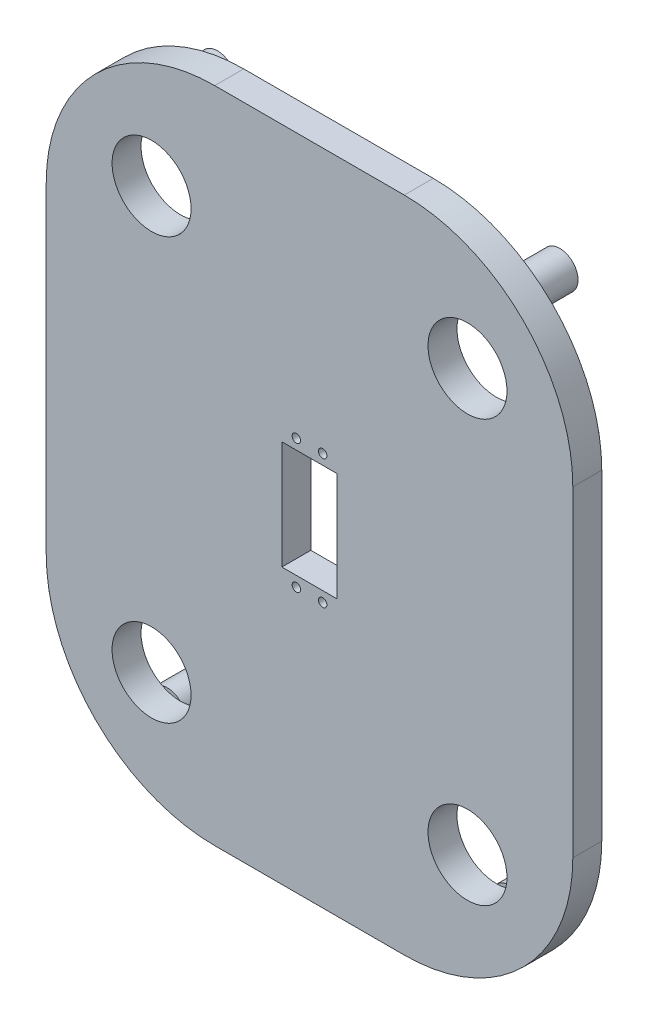
SolidWorks part; units mm, degrees
ref_plane "Front Plane" through (0, 0, 0) normal (0, 0, 1) x (1, 0, 0)
ref_plane "Top Plane" through (0, 0, 0) normal (0, 1, 0) x (1, 0, 0)
ref_plane "Right Plane" through (0, 0, 0) normal (1, 0, 0) x (0, 0, -1)
sketch "Sketch1" plane through (0, 0, 0) normal (0, 0, 1) x (1, 0, 0)
  line L0 (-20, 10) -> (15, 10) construction
  line L2 (-20, 70) -> (-20, -50)
  line L4 (15, 70) -> (15, -50)
  line L5 (-13, 75.5) -> (8, 75.5)
  line L6 (-13, 75.5) -> (-13, 34.5)
  line L7 (-13, 34.5) -> (8, 34.5)
  line L8 (8, 75.5) -> (8, 34.5)
  line L9 (-2.5, 75.5) -> (-2.5, 79.5) construction
  line L10 (-2.5, 79.5) -> (-7.5, 79.5) construction
  line L11 (-2.5, 79.5) -> (2.5, 79.5) construction
  line L12 (-13, 55) -> (8, 55) construction
  line L13 (-7.5, 79.5) -> (-7.5, 30.5) construction
  arc A3 (15, 70) -> (-20, 70) centre (-2.5, 70) ccw
  arc A4 (-20, -50) -> (15, -50) centre (-2.5, -50) ccw
  circle A5 centre (-7.5, 79.5) radius 1.6
  circle A6 centre (2.5, 79.5) radius 1.6
  circle A7 centre (2.5, 30.5) radius 1.6
  circle A8 centre (-7.5, 30.5) radius 1.6
  point P0 (0, 0)
  point P7 (-2.5, 87.5)
  dimension "D4" = 41
  dimension "D5" = 21
  dimension "D7" = 12
  dimension "D11" = 3.2
  dimension "D1" = 120
  dimension "D2" = 35
  dimension "D3" = 120
  dimension "D6" = 7
  dimension "D8" = 4
  dimension "D10" = 5
sketch "Sketch2" plane through (0, 0, 0) normal (0, 0, 1) x (1, 0, 0)
sketch "Sketch3" plane through (0, 0, 0) normal (0, 0, 1) x (1, 0, 0)
extrude "Boss-Extrude1" add sketch "Sketch1" along normal blind 11
sketch "Sketch6" plane through (0, 0, 11) normal (0, 0, 1) x (1, 0, 0)
  line L0 (8, 34.5) -> (8, 75.5) construction
  line L1 (-13, 34.5) -> (8, 34.5) construction
  line L2 (15, -50) -> (15, 70)
  line L3 (-20, 70) -> (-20, -50)
  line L4 (15, -50) -> (15, 70)
  line L5 (-20, 70) -> (-20, -50)
  line L6 (8, 75.5) -> (-13, 75.5) construction
  line L7 (-13, 75.5) -> (-13, 34.5) construction
  line L8 (8, 34.5) -> (8, 75.5)
  line L9 (-13, 34.5) -> (8, 34.5)
  line L10 (8, 75.5) -> (-13, 75.5)
  line L11 (-13, 75.5) -> (-13, 34.5)
  line L12 (-13, 34.5) -> (8, 34.5)
  line L13 (-13, 75.6) -> (8, 75.6)
  line L14 (-13, 75.6) -> (-13, 34.4)
  line L15 (-13, 34.4) -> (8, 34.4)
  line L16 (8, 75.6) -> (8, 34.4)
  line L17 (-13, 75.5) -> (8, 75.5)
  arc A2 (-20, -50) -> (15, -50) centre (-2.5, -50) ccw
  arc A3 (15, 70) -> (-20, 70) centre (-2.5, 70) ccw
  arc A4 (-20, -50) -> (15, -50) centre (-2.5, -50) ccw
  arc A5 (15, 70) -> (-20, 70) centre (-2.5, 70) ccw
  line M15 (8, 34.5) -> (-13, 34.5)
  line M17 (-13, 75.5) -> (8, 75.5)
  dimension "D2" = 0.1
  dimension "D3" = 0.1
  dimension "D1" = 0
extrude "Cut-Extrude1" cut sketch "Sketch6" against normal through all contours L16 L13 L14 M17 | L16 L14 L15 M15
sketch "Sketch7" plane through (0, 0, 0) normal (0, 0, -1) x (-1, 0, 0)
  line L0 (13, 34.4) -> (-8, 34.4) construction
  line L1 (13, 75.6) -> (13, 34.4) construction
  line L2 (13, 75.6) -> (-8, 75.6) construction
  line L3 (-8, 34.4) -> (-8, 75.6) construction
  line L4 (13, 34.4) -> (-8, 34.4)
  line L5 (13, 75.6) -> (13, 34.4)
  line L6 (13, 75.6) -> (-8, 75.6)
  line L7 (-8, 34.4) -> (-8, 75.6)
  line L8 (-15, 10) -> (20, 10) construction
  line L9 (-15, -50) -> (-15, 70) construction
  line L10 (20, 70) -> (20, -50) construction
  line L11 (13, -55.6) -> (13, -14.4)
  line L12 (13, -55.6) -> (-8, -55.6)
  line L13 (-8, -14.4) -> (-8, -55.6)
  line L14 (13, -14.4) -> (-8, -14.4)
  circle A0 centre (7.5, 79.5) radius 1.6 construction
  circle A1 centre (-2.5, 79.5) radius 1.6 construction
  circle A2 centre (7.5, 30.5) radius 1.6 construction
  circle A3 centre (-2.5, 30.5) radius 1.6 construction
  circle A4 centre (7.5, 79.5) radius 1.6
  circle A5 centre (-2.5, 79.5) radius 1.6
  circle A6 centre (7.5, 30.5) radius 1.6
  circle A7 centre (-2.5, 30.5) radius 1.6
  circle A8 centre (7.5, -10.5) radius 1.6
  circle A9 centre (-2.5, -10.5) radius 1.6
  circle A10 centre (-2.5, -59.5) radius 1.6
  circle A11 centre (7.5, -59.5) radius 1.6
extrude "Cut-Extrude2" cut sketch "Sketch7" against normal up to surface (11 mm away) contours L11 L14 L13 L12 | A9 | A8 | A10 | A11 up to face at (4.1, 30.5, 11)
sketch "Sketch8" plane through (0, 0, 11) normal (0, 0, 1) x (1, 0, 0)
  line L0 (-2.5, 75.6) -> (-2.5, 34.4) construction
  line L1 (-13, 75.6) -> (8, 75.6) construction
  line L2 (-13, 34.4) -> (8, 34.4) construction
  line L3 (-13, 55) -> (8, 55) construction
  line L4 (-13, 75.6) -> (-13, 34.4) construction
  line L5 (8, 34.4) -> (8, 75.6) construction
  line L7 (-102.5, 180) -> (97.5, 180)
  line L8 (-102.5, 180) -> (-102.5, -70)
  line L9 (-102.5, -70) -> (97.5, -70)
  line L10 (97.5, 180) -> (97.5, -70)
  line L11 (-102.5, 180) -> (97.5, -70) construction
  line L12 (-102.5, -70) -> (97.5, 180) construction
  point P12 (-2.5, 55)
  circle M5 centre (2.5, -59.5) radius 1.6
  circle M6 centre (2.5, -10.5) radius 1.6
  line M7 (-13, -14.4) -> (8, -14.4)
  line M8 (8, -14.4) -> (8, -55.6)
  line M9 (8, -55.6) -> (-13, -55.6)
  line M10 (-13, -55.6) -> (-13, -14.4)
  arc M13 (-20, -50) -> (15, -50) centre (-2.5, -50) ccw
  line M14 (15, -50) -> (15, 70)
  arc M15 (15, 70) -> (-20, 70) centre (-2.5, 70) ccw
  line M16 (-20, 70) -> (-20, -50)
  circle M23 centre (-7.5, -10.5) radius 1.6
  circle M24 centre (-7.5, -59.5) radius 1.6
  dimension "D1" = 250
  dimension "D2" = 200
extrude "Boss-Extrude2" add sketch "Sketch8" against normal up to surface (21 mm away) contours L10 L7 L8 L9 M13 M16 M15 M14 | M7 M10 M9 M8 | M24 | M5 | M23 | M6
fillet "Fillet1" radius 64 1 edges at (-102.5, 180, 5.5)
fillet "Fillet2" radius 64 1 edges at (97.5, 180, 5.5)
fillet "Fillet3" radius 64 1 edges at (97.5, -70, 5.5)
fillet "Fillet4" radius 64 1 edges at (-102.5, -70, 5.5)
sketch "Sketch9" plane through (0, 0, 11) normal (0, 0, 1) x (1, 0, 0)
  line L0 (-38.5, 180) -> (33.5, 180) construction
  line L1 (-102.5, 55) -> (97.5, 55) construction
  line L2 (-102.5, 116) -> (-102.5, -6) construction
  line L3 (97.5, 116) -> (97.5, -6) construction
  line L8 (-102.5, 116) -> (-102.5, -6)
  line L9 (-38.5, -70) -> (33.5, -70)
  line L10 (97.5, -6) -> (97.5, 116)
  line L11 (33.5, 180) -> (-38.5, 180)
  line L12 (-102.5, 116) -> (-102.5, -6)
  line L13 (-38.5, -70) -> (33.5, -70)
  line L14 (97.5, -6) -> (97.5, 116)
  line L15 (33.5, 180) -> (-38.5, 180)
  arc A0 (-18.3486, 180) -> (13.3486, 180) centre (-2.5, 180) ccw
  arc A1 (-18.3486, -70) -> (13.3486, -70) centre (-2.5, -70) cw
  arc A6 (-102.5, -6) -> (-38.5, -70) centre (-38.5, -6) ccw
  arc A7 (33.5, -70) -> (97.5, -6) centre (33.5, -6) ccw
  arc A8 (97.5, 116) -> (33.5, 180) centre (33.5, 116) ccw
  arc A9 (-38.5, 180) -> (-102.5, 116) centre (-38.5, 116) ccw
  arc A10 (-102.5, -6) -> (-38.5, -70) centre (-38.5, -6) ccw
  arc A11 (33.5, -70) -> (97.5, -6) centre (33.5, -6) ccw
  arc A12 (97.5, 116) -> (33.5, 180) centre (33.5, 116) ccw
  arc A13 (-38.5, 180) -> (-102.5, 116) centre (-38.5, 116) ccw
  dimension "D1" = 0
sketch "Sketch12" plane through (0, 0, 0) normal (0, 0, -1) x (-1, 0, 0)
  line L0 (2.5, 180) -> (2.5, -70)
  line L1 (-97.5, 55) -> (102.5, 55)
  circle A0 centre (-62.5, 155) radius 6.9335
  circle A1 centre (67.5, 155) radius 6.9335
  circle A2 centre (67.5, -45) radius 6.9335
  circle A3 centre (-62.5, -45) radius 6.9335
  dimension "D1" = 65
  dimension "D2" = 100
extrude "Boss-Extrude3" add sketch "Sketch12" along normal blind 19.05 contours A1 | A3 | A2 | A0
sketch "Sketch13" plane through (0, 0, 11) normal (0, 0, 1) x (1, 0, 0)
  line L0 (-102.5, 55) -> (97.5, 55) construction
  line L1 (-62.5, 115) -> (57.5, 115)
  line L2 (-62.5, 115) -> (-62.5, -5)
  line L3 (-62.5, -5) -> (57.5, -5)
  line L4 (57.5, 115) -> (57.5, -5)
  line L5 (-62.5, 115) -> (57.5, -5) construction
  line L6 (-62.5, -5) -> (57.5, 115) construction
  line L7 (-62.5, 115) -> (-62.5, 135) construction
  line L8 (-2.5, 180) -> (-2.5, -70) construction
  line L9 (-102.5, 55) -> (97.5, 55) construction
  circle A0 centre (-62.5, 135) radius 15
  circle A1 centre (57.5, 135) radius 15
  circle A2 centre (57.5, -25) radius 15
  circle A3 centre (-62.5, -25) radius 15
  point P0 (-2.5, 55)
  dimension "D4" = 30
  dimension "D1" = 120
  dimension "D2" = 120
  dimension "D3" = 20
extrude "Cut-Extrude3" cut sketch "Sketch13" against normal up to surface (11 mm away) contours A0 | A1 | A3 | L4 L1 L2 L3 A0 A2 L8 A1 L9 L7
